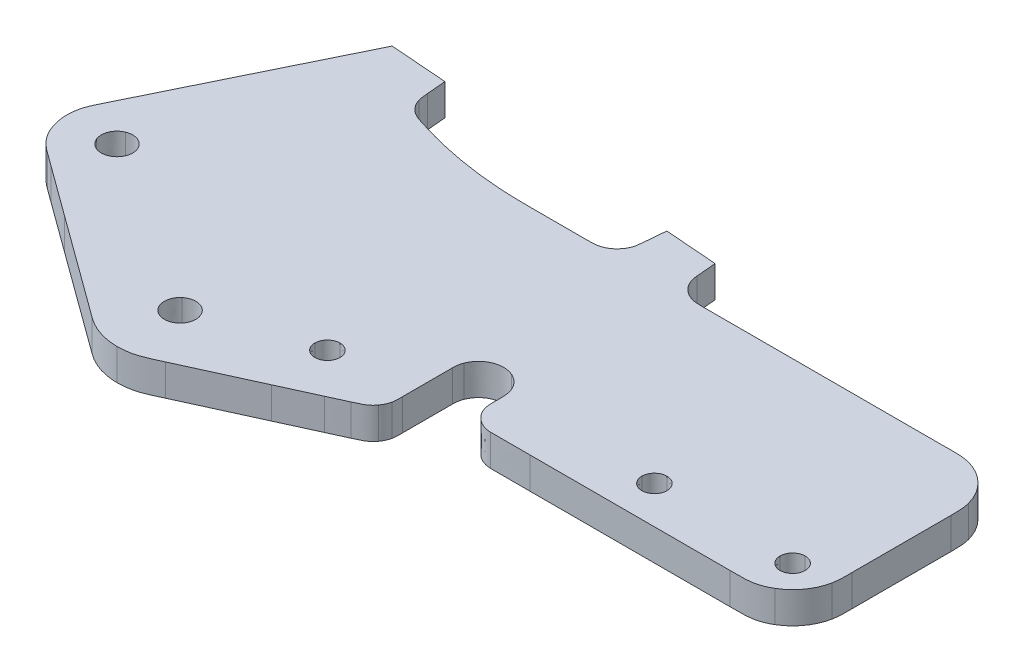
SolidWorks part; units mm, degrees
ref_plane "Front Plane" through (0, 0, 0) normal (0, 0, 1) x (1, 0, 0)
ref_plane "Top Plane" through (0, 0, 0) normal (0, 1, 0) x (1, 0, 0)
ref_plane "Right Plane" through (0, 0, 0) normal (1, 0, 0) x (0, 0, -1)
sketch "Sketch1" plane through (0, 0, 0) normal (0, 1, 0) x (1, 0, 0)
  line L0 (26.2542, 100.7033) -> (40.6892, 99.5939)
  line L1 (101.4193, 94.9221) -> (114.6416, 93.9093)
  line L2 (47.6413, 3.4801) -> (47.6414, 3.4827)
  spline S0 degree 3 poles (47.6414, 3.4827) (39.1389, 9.6839) (30.6295, 15.885) (22.127, 22.0862) knots 0 0 0 0 1 1 1 1
  spline S1 degree 3 poles (22.127, 22.0862) (17.8826, 25.1868) (13.6314, 28.2805) (9.387, 31.381) knots 0 0 0 0 1 1 1 1
  spline S2 degree 3 poles (9.387, 31.381) (8.3259, 32.1527) (7.2649, 32.9314) (6.2038, 33.703) knots 0 0 0 0 1 1 1 1
  spline S3 degree 3 poles (6.2038, 33.703) (5.1358, 34.4816) (4.1092, 35.274) (3.241, 36.2938) knots 0 0 0 0 1 1 1 1
  spline S4 degree 3 poles (3.241, 36.2938) (1.5184, 38.3195) (0.478, 40.8275) (0.2644, 43.4803) knots 0 0 0 0 1 1 1 1
  spline S5 degree 3 poles (0.2644, 43.4803) (0.1542, 44.8307) (0.2503, 46.1192) (0.5607, 47.4421) knots 0 0 0 0 1 1 1 1
  spline S6 degree 3 poles (0.5607, 47.4421) (0.8639, 48.7374) (1.4082, 49.9088) (1.987, 51.0939) knots 0 0 0 0 1 1 1 1
  spline S7 degree 3 poles (1.987, 51.0939) (3.1445, 53.4435) (4.2883, 55.793) (5.4458, 58.1494) knots 0 0 0 0 1 1 1 1
  spline S8 degree 3 poles (5.4458, 58.1494) (7.7541, 62.8762) (10.0691, 67.6097) (12.3774, 72.3363) knots 0 0 0 0 1 1 1 1
  spline S9 degree 3 poles (12.3774, 72.3363) (17.0007, 81.7897) (21.624, 91.2499) (26.2542, 100.7033) knots 0 0 0 0 1 1 1 1
  spline S10 degree 3 poles (40.6892, 99.5939) (40.8338, 97.9679) (40.9716, 96.3487) (41.1164, 94.7226) knots 0 0 0 0 1 1 1 1
  spline S11 degree 3 poles (41.1164, 94.7226) (41.1853, 93.9164) (41.2197, 93.1172) (41.454, 92.3317) knots 0 0 0 0 1 1 1 1
  spline S12 degree 3 poles (41.454, 92.3317) (41.6951, 91.498) (42.0741, 90.7883) (42.6184, 90.1131) knots 0 0 0 0 1 1 1 1
  spline S13 degree 3 poles (42.6184, 90.1131) (43.7691, 88.7006) (45.2091, 88.1907) (46.8214, 87.6808) knots 0 0 0 0 1 1 1 1
  spline S14 degree 3 poles (46.8214, 87.6808) (48.3717, 87.1779) (49.9358, 86.7231) (51.5205, 86.3028) knots 0 0 0 0 1 1 1 1
  spline S15 degree 3 poles (51.5205, 86.3028) (57.9078, 84.6009) (64.3087, 83.5467) (70.9027, 83.1058) knots 0 0 0 0 1 1 1 1
  spline S16 degree 3 poles (70.9027, 83.1058) (74.1824, 82.8853) (77.4552, 82.8782) (80.7349, 82.8782) knots 0 0 0 0 1 1 1 1
  spline S17 degree 3 poles (80.7349, 82.8782) (84.0147, 82.8782) (87.2944, 82.8782) (90.5742, 82.8782) knots 0 0 0 0 1 1 1 1
  spline S18 degree 3 poles (90.5742, 82.8782) (91.146, 82.8782) (94.7841, 82.8583) (95.3559, 82.9332) knots 0 0 0 0 1 1 1 1
  spline S19 degree 3 poles (95.3559, 82.9332) (97.0441, 83.1467) (98.5737, 84.0357) (99.6072, 85.393) knots 0 0 0 0 1 1 1 1
  spline S20 degree 3 poles (99.6072, 85.393) (100.813, 86.9778) (100.8336, 88.1973) (100.9921, 90.037) knots 0 0 0 0 1 1 1 1
  spline S21 degree 3 poles (100.9921, 90.037) (101.1368, 91.67) (101.2815, 93.2961) (101.4193, 94.9221) knots 0 0 0 0 1 1 1 1
  spline S22 degree 3 poles (114.6416, 93.9093) (114.7863, 92.235) (114.931, 90.5675) (115.0757, 88.8932) knots 0 0 0 0 1 1 1 1
  spline S23 degree 3 poles (115.0757, 88.8932) (115.248, 86.9985) (115.8336, 85.6411) (117.3081, 84.3939) knots 0 0 0 0 1 1 1 1
  spline S24 degree 3 poles (117.3081, 84.3939) (118.7688, 83.1537) (120.2571, 82.8781) (122.0761, 82.8781) knots 0 0 0 0 1 1 1 1
  spline S25 degree 3 poles (122.0761, 82.8781) (123.7573, 82.8781) (125.4316, 82.8781) (127.1128, 82.8781) knots 0 0 0 0 1 1 1 1
  spline S26 degree 3 poles (127.1128, 82.8781) (133.8307, 82.8781) (140.5487, 82.8781) (147.2666, 82.8781) knots 0 0 0 0 1 1 1 1
  spline S27 degree 3 poles (147.2666, 82.8781) (154.019, 82.8781) (160.7783, 82.8781) (167.5307, 82.8781) knots 0 0 0 0 1 1 1 1
  spline S28 degree 3 poles (167.5307, 82.8781) (170.9069, 82.8781) (174.2831, 82.8781) (177.6662, 82.8781) knots 0 0 0 0 1 1 1 1
  spline S29 degree 3 poles (177.6662, 82.8781) (179.3543, 82.8781) (181.0424, 82.8781) (182.7304, 82.8781) knots 0 0 0 0 1 1 1 1
  spline S30 degree 3 poles (182.7304, 82.8781) (184.3979, 82.8781) (186.0653, 82.9677) (187.7327, 82.8431) knots 0 0 0 0 1 1 1 1
  spline S31 degree 3 poles (187.7327, 82.8431) (191.2467, 82.5882) (194.492, 80.8932) (196.7106, 78.1509) knots 0 0 0 0 1 1 1 1
  spline S32 degree 3 poles (196.7106, 78.1509) (197.8475, 76.7385) (198.6054, 75.2571) (199.0809, 73.5069) knots 0 0 0 0 1 1 1 1
  spline S33 degree 3 poles (199.0809, 73.5069) (199.5218, 71.8877) (199.5218, 70.2892) (199.5218, 68.6493) knots 0 0 0 0 1 1 1 1
  spline S34 degree 3 poles (199.5218, 68.6493) (199.5218, 61.9934) (199.5218, 55.3237) (199.5218, 48.6609) knots 0 0 0 0 1 1 1 1
  spline S35 degree 3 poles (199.5218, 48.6609) (199.5218, 46.9935) (199.5218, 45.326) (199.5218, 43.6655) knots 0 0 0 0 1 1 1 1
  spline S36 degree 3 poles (199.5218, 43.6655) (199.5218, 42.0325) (199.5977, 40.4202) (199.2669, 38.7941) knots 0 0 0 0 1 1 1 1
  spline S37 degree 3 poles (199.2669, 38.7941) (198.5434, 35.2871) (196.3799, 32.2484) (193.3, 30.4225) knots 0 0 0 0 1 1 1 1
  spline S38 degree 3 poles (193.3, 30.4225) (189.8273, 28.3693) (187.3193, 28.6449) (183.5986, 28.6449) knots 0 0 0 0 1 1 1 1
  spline S39 degree 3 poles (183.5986, 28.6449) (180.2706, 28.6449) (176.9357, 28.6449) (173.6078, 28.6449) knots 0 0 0 0 1 1 1 1
  spline S40 degree 3 poles (173.6078, 28.6449) (160.0961, 28.6449) (146.5845, 28.6449) (133.0728, 28.6449) knots 0 0 0 0 1 1 1 1
  spline S41 degree 3 poles (133.0728, 28.6449) (129.7724, 28.6449) (126.472, 28.5689) (123.1647, 28.6499) knots 0 0 0 0 1 1 1 1
  spline S42 degree 3 poles (123.1647, 28.6499) (121.4353, 28.6899) (119.8023, 29.4354) (118.631, 30.7169) knots 0 0 0 0 1 1 1 1
  spline S43 degree 3 poles (118.631, 30.7169) (117.3632, 32.1156) (116.9773, 33.535) (116.9773, 35.3609) knots 0 0 0 0 1 1 1 1
  spline S44 degree 3 poles (116.9773, 35.3609) (116.9773, 36.739) (117.1013, 38.8543) (116.6121, 40.2392) knots 0 0 0 0 1 1 1 1
  spline S45 degree 3 poles (116.6121, 40.2392) (116.0196, 41.9273) (114.7449, 43.2846) (113.0981, 43.9805) knots 0 0 0 0 1 1 1 1
  spline S46 degree 3 poles (113.0981, 43.9805) (109.7839, 45.3792) (105.9943, 43.767) (104.699, 40.4115) knots 0 0 0 0 1 1 1 1
  spline S47 degree 3 poles (104.699, 40.4115) (104.3889, 39.6122) (104.2718, 38.8198) (104.2718, 37.9723) knots 0 0 0 0 1 1 1 1
  spline S48 degree 3 poles (104.2718, 37.9723) (104.2718, 37.1248) (104.2718, 36.2842) (104.2718, 35.4436) knots 0 0 0 0 1 1 1 1
  spline S49 degree 3 poles (104.2718, 35.4436) (104.2718, 33.7555) (104.2718, 32.0674) (104.2718, 30.3793) knots 0 0 0 0 1 1 1 1
  spline S50 degree 3 poles (104.2718, 30.3793) (104.2718, 28.6912) (104.2718, 27.0031) (104.2718, 25.315) knots 0 0 0 0 1 1 1 1
  spline S51 degree 3 poles (104.2718, 25.315) (104.2718, 24.4813) (104.3133, 23.6545) (104.134, 22.8139) knots 0 0 0 0 1 1 1 1
  spline S52 degree 3 poles (104.134, 22.8139) (103.9411, 21.9319) (103.6035, 21.174) (103.0798, 20.4436) knots 0 0 0 0 1 1 1 1
  spline S53 degree 3 poles (103.0798, 20.4436) (101.9843, 18.9209) (100.4891, 18.3422) (98.9181, 17.6256) knots 0 0 0 0 1 1 1 1
  spline S54 degree 3 poles (98.9181, 17.6256) (97.3885, 16.9297) (95.852, 16.2269) (94.3155, 15.531) knots 0 0 0 0 1 1 1 1
  spline S55 degree 3 poles (94.3155, 15.531) (91.2425, 14.1253) (88.1694, 12.7266) (85.1033, 11.3279) knots 0 0 0 0 1 1 1 1
  spline S56 degree 3 poles (85.1033, 11.3279) (78.9917, 8.5443) (72.8801, 5.7607) (66.7754, 2.977) knots 0 0 0 0 1 1 1 1
  spline S57 degree 3 poles (66.7754, 2.977) (63.3027, 1.3992) (61.1875, 0.1934) (57.1567, 0.221) knots 0 0 0 0 1 1 1 1
  spline S58 degree 3 poles (57.1567, 0.221) (53.7185, 0.251) (50.3767, 1.3923) (47.6413, 3.4801) knots 0 0 0 0 1 1 1 1
  spline S59 degree 3 poles (193.176, 38.1335) (193.176, 39.8835) (191.7566, 41.3098) (189.9996, 41.3098) knots 0 0 0 0 1 1 1 1
  spline S60 degree 3 poles (189.9996, 41.3098) (188.2495, 41.3098) (186.8232, 39.8835) (186.8232, 38.1335) knots 0 0 0 0 1 1 1 1
  spline S61 degree 3 poles (186.8232, 38.1335) (186.8232, 36.3764) (188.2495, 34.9571) (189.9996, 34.9571) knots 0 0 0 0 1 1 1 1
  spline S62 degree 3 poles (189.9996, 34.9571) (191.7566, 34.9571) (193.176, 36.3764) (193.176, 38.1335) knots 0 0 0 0 1 1 1 1
  spline S63 degree 3 poles (60.3193, 18.648) (58.9137, 20.3292) (56.4057, 20.5497) (54.7314, 19.137) knots 0 0 0 0 1 1 1 1
  spline S64 degree 3 poles (54.7314, 19.137) (53.0502, 17.7314) (52.8297, 15.2234) (54.2353, 13.549) knots 0 0 0 0 1 1 1 1
  spline S65 degree 3 poles (54.2353, 13.549) (55.6478, 11.8678) (58.1558, 11.6542) (59.8301, 13.06) knots 0 0 0 0 1 1 1 1
  spline S66 degree 3 poles (59.8301, 13.06) (61.5113, 14.4656) (61.7249, 16.9737) (60.3193, 18.648) knots 0 0 0 0 1 1 1 1
  spline S67 degree 3 poles (87.8043, 25.9654) (87.8043, 27.7155) (86.3849, 29.1349) (84.6348, 29.1349) knots 0 0 0 0 1 1 1 1
  spline S68 degree 3 poles (84.6348, 29.1349) (82.8778, 29.1349) (81.4584, 27.7155) (81.4584, 25.9654) knots 0 0 0 0 1 1 1 1
  spline S69 degree 3 poles (81.4584, 25.9654) (81.4584, 24.2084) (82.8778, 22.789) (84.6348, 22.789) knots 0 0 0 0 1 1 1 1
  spline S70 degree 3 poles (84.6348, 22.789) (86.3849, 22.789) (87.8043, 24.2084) (87.8043, 25.9654) knots 0 0 0 0 1 1 1 1
  spline S71 degree 3 poles (158.2496, 38.1335) (158.2496, 39.8835) (156.8302, 41.3098) (155.0732, 41.3098) knots 0 0 0 0 1 1 1 1
  spline S72 degree 3 poles (155.0732, 41.3098) (153.3231, 41.3098) (151.8969, 39.8835) (151.8969, 38.1335) knots 0 0 0 0 1 1 1 1
  spline S73 degree 3 poles (151.8969, 38.1335) (151.8969, 36.3764) (153.3231, 34.9571) (155.0732, 34.9571) knots 0 0 0 0 1 1 1 1
  spline S74 degree 3 poles (155.0732, 34.9571) (156.8302, 34.9571) (158.2496, 36.3764) (158.2496, 38.1335) knots 0 0 0 0 1 1 1 1
  spline S75 degree 3 poles (16.5804, 46.0434) (15.7398, 48.0622) (13.4178, 49.0269) (11.399, 48.1862) knots 0 0 0 0 1 1 1 1
  spline S76 degree 3 poles (11.399, 48.1862) (9.3732, 47.3525) (8.4086, 45.0305) (9.2492, 43.0048) knots 0 0 0 0 1 1 1 1
  spline S77 degree 3 poles (9.2492, 43.0048) (10.0898, 40.9791) (12.4118, 40.0144) (14.4307, 40.8551) knots 0 0 0 0 1 1 1 1
  spline S78 degree 3 poles (14.4307, 40.8551) (16.4564, 41.6957) (17.421, 44.0177) (16.5804, 46.0434) knots 0 0 0 0 1 1 1 1
extrude "Boss-Extrude1" add sketch "Sketch1" along normal blind 7.9375 contours L0 S10 S11 S12 S13 S14 S15 S16 S17 S18 S19 S20 S21 L1 S22 S23 S24 S25 S26 S27 S28 S29 S30 S31 S32 S33 S34 S35 S36 S37 S38 S39 S40 S41 S42 S43 S44 S45 S46 S47 S48 S49 S50 S51 S52 S53 S54 S55 S56 S57 S58 L2 S0 S1 S2 S3 S4 S5 S6 S7 S8 S9
sketch "Sketch2" plane through (7.8204, 0, -102.092) normal (0.0764, 0, -0.9971) x (-0.9971, 0, -0.0764)
  line L0 (-100.5036, 3.9688) -> (-26.3356, 3.9688) construction
  line L1 (-93.8731, 7.9375) -> (-107.1341, 7.9375) construction
  line L2 (-93.8731, 7.9375) -> (-93.8731, 0) construction
  line L3 (-93.8731, 0) -> (-107.1341, 0) construction
  line L4 (-107.1341, 7.9375) -> (-107.1341, 0) construction
  line L5 (-93.8731, 7.9375) -> (-107.1341, 0) construction
  line L6 (-93.8731, 0) -> (-107.1341, 7.9375) construction
  point P4 (-100.5036, 3.9688)
  dimension "D1" = 74.168
sketch "Sketch5" plane through (7.8481, 0, -102.1179) normal (0.0766, 0, -0.9971) x (-0.9971, 0, -0.0766)
  point P0 (-26.31, 3.9688)
hole_wizard "M6x1.0 Tapped Hole5" positions "3DSketch2" profile "Sketch4" tap size "M6x1.0" standard "ANSI Metric"
sketch3d "3DSketch2"
  point P0 (108.0305, 3.9688, -94.4157)
  point P3 (34.0808, 3.9688, -100.1018)
sketch "Sketch4" plane through (108.0305, 3.9688, -94.4157) normal (0, 1, 0) x (-0.9971, 0, -0.0764)
  line L0 (0, 0) -> (0, 13.5022)
  line L1 (0, 13.5022) -> (2.5, 12)
  line L2 (2.5, 12) -> (2.5, 0.525)
  line L3 (2.5, 0.525) -> (3.025, 0)
  line L5 (3.025, 0) -> (0, 0)
  line L6 (-2.5, 0.525) -> (-3.025, 0) construction
  line L10 (0, 13.5022) -> (-2.5, 12) construction
  line L11 (0, -6.35) -> (0, 107.95) construction
  dimension "Tap Drill Dia." = 5
  dimension "Tap Drill Depth" = 12
  dimension "Near C'Sink Dia." = 6.05
  dimension "Near C'Sink Angle" = 90
  dimension "Drill Angle" = 118
cosmetic thread "Hole Thread2" parameters "D1"=11.938, "D2"=6
cosmetic thread "Hole Thread3" parameters "D1"=11.938, "D2"=6
sketch "Sketch6" plane through (0, 7.9375, 0) normal (0, 1, 0) x (1, 0, 0)
  circle A0 centre (12.9155, 44.5224) radius 3.968
  circle A1 centre (57.2711, 16.0995) radius 3.9733
  circle A2 centre (84.6314, 25.962) radius 3.1729
  circle A3 centre (155.0732, 38.1335) radius 3.1764
  circle A4 centre (189.9996, 38.1335) radius 3.1764
  spline S0 degree 3 poles (60.3193, 18.648) (58.9137, 20.3292) (56.4057, 20.5497) (54.7314, 19.137) knots 0 0 0 0 1 1 1 1 construction
